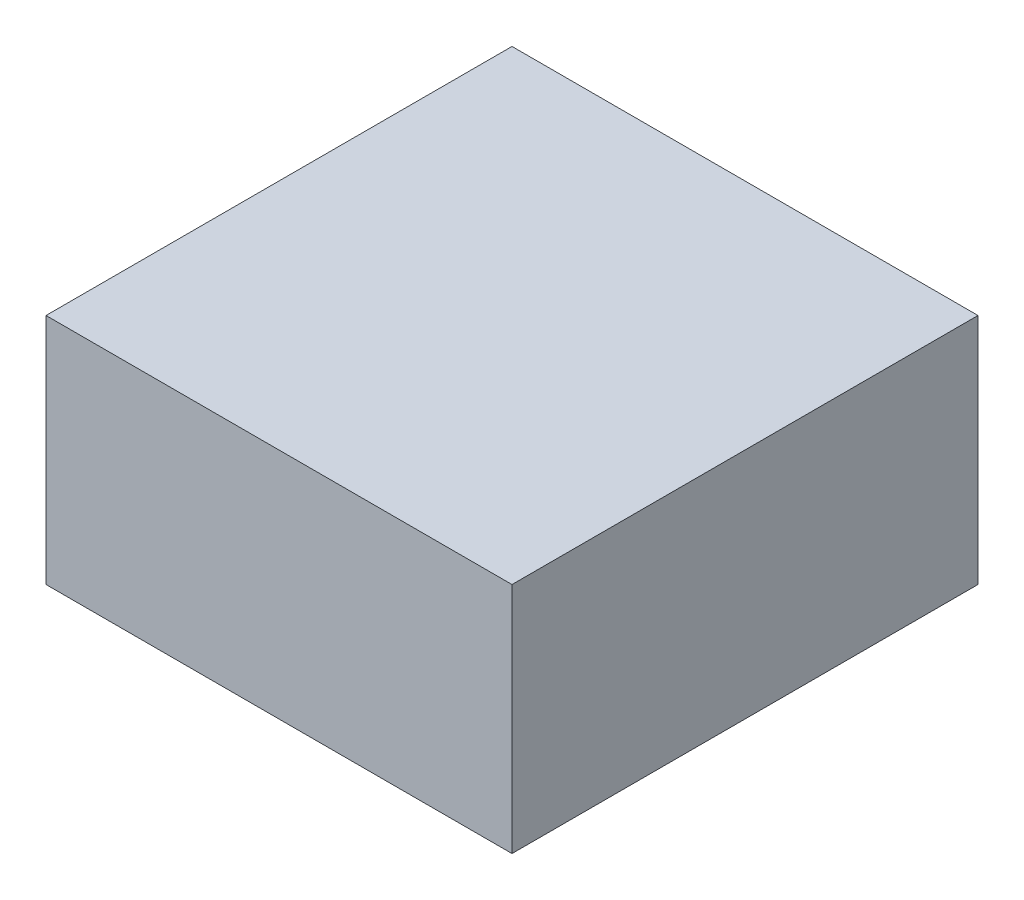
SolidWorks part; units mm, degrees
ref_plane "Front Plane" through (0, 0, 0) normal (0, 0, 1) x (1, 0, 0)
ref_plane "Top Plane" through (0, 0, 0) normal (0, 1, 0) x (1, 0, 0)
ref_plane "Right Plane" through (0, 0, 0) normal (1, 0, 0) x (0, 0, -1)
sketch "Sketch1" plane through (0, 0, 0) normal (0, 1, 0) x (1, 0, 0)
  line L1 (-43.18, 43.18) -> (43.18, 43.18)
  line L2 (-43.18, 43.18) -> (-43.18, -43.18)
  line L3 (-43.18, -43.18) -> (43.18, -43.18)
  line L4 (43.18, 43.18) -> (43.18, -43.18)
  point P4 (-43.18, 0)
  point P5 (43.18, 0)
  point P7 (0, -43.18)
  dimension "D1" = 86.36
  dimension "D2" = 86.36
extrude "Boss-Extrude1" add sketch "Sketch1" against normal blind 43.18
sketch "Sketch2" plane through (0, -43.18, 0) normal (0, -1, 0) x (-1, 0, 0)
  line L0 (43.18, 43.18) -> (43.18, -43.18) construction
  line L1 (-40.64, 40.64) -> (40.64, 40.64)
  line L2 (-40.64, 40.64) -> (-40.64, -40.64)
  line L3 (-40.64, -40.64) -> (40.64, -40.64)
  line L4 (40.64, 40.64) -> (40.64, -40.64)
  line L5 (-43.18, 43.18) -> (43.18, 43.18) construction
  point P8 (40.64, 0)
  point P9 (43.18, 0)
  point P10 (0, 40.64)
  point P11 (0, 43.18)
  dimension "D1" = 2.54
  dimension "D2" = 2.54
extrude "Cut-Extrude2" cut sketch "Sketch2" against normal offset from surface (35.56 mm away) 7.62 up to face at (0, 0, 0)
sketch "Sketch6" plane through (0, -7.62, 0) normal (0, -1, 0) x (-1, 0, 0)
  line L0 (-27.94, 38.1) -> (27.94, 38.1)
  line L1 (38.1, 27.94) -> (38.1, -27.94)
  line L2 (27.94, -38.1) -> (-27.94, -38.1)
  line L3 (-38.1, -27.94) -> (-38.1, 27.94)
  line L4 (40.64, 40.64) -> (-40.64, 40.64) construction
  line L5 (40.64, -40.64) -> (40.64, 40.64) construction
  line L6 (-40.64, 40.64) -> (-40.64, -40.64) construction
  line L7 (-40.64, -40.64) -> (40.64, -40.64) construction
  line L9 (-40.64, 40.64) -> (40.64, 40.64)
  line L10 (-40.64, 40.64) -> (-40.64, -40.64)
  line L11 (-40.64, -40.64) -> (40.64, -40.64)
  line L12 (40.64, 40.64) -> (40.64, -40.64)
  arc A0 (-30.48, 35.56) -> (-35.56, 30.48) centre (-35.56, 35.56) cw
  arc A1 (30.48, 35.56) -> (35.56, 30.48) centre (35.56, 35.56) ccw
  arc A2 (35.56, -30.48) -> (30.48, -35.56) centre (35.56, -35.56) ccw
  arc A3 (-30.48, -35.56) -> (-35.56, -30.48) centre (-35.56, -35.56) ccw
  arc A4 (-35.56, 30.48) -> (-38.1, 27.94) centre (-35.56, 27.94) ccw
  arc A5 (-35.56, -30.48) -> (-38.1, -27.94) centre (-35.56, -27.94) cw
  arc A6 (-30.48, -35.56) -> (-27.94, -38.1) centre (-27.94, -35.56) ccw
  arc A7 (30.48, -35.56) -> (27.94, -38.1) centre (27.94, -35.56) cw
  arc A8 (35.56, -30.48) -> (38.1, -27.94) centre (35.56, -27.94) ccw
  arc A9 (35.56, 30.48) -> (38.1, 27.94) centre (35.56, 27.94) cw
  arc A10 (30.48, 35.56) -> (27.94, 38.1) centre (27.94, 35.56) ccw
  arc A11 (-30.48, 35.56) -> (-27.94, 38.1) centre (-27.94, 35.56) cw
  circle A12 centre (-35.56, 35.56) radius 1.016
  circle A13 centre (35.56, 35.56) radius 1.016
  circle A14 centre (35.56, -35.56) radius 1.016
  circle A15 centre (-35.56, -35.56) radius 1.016
  point P45 (0, 0)
  point P46 (0, 0)
  point P47 (15.24, 27.94)
  point P48 (15.24, 27.94)
  point P49 (12.8505, 44.1061)
  point P50 (40.64, 27.94)
  dimension "D1" = 5.08
  dimension "D6" = 2.54
  dimension "D7" = 2.032
  dimension "D2" = 2.54
  dimension "D3" = 2.54
  dimension "D4" = 2.54
  dimension "D5" = 2.54
extrude "Boss-Extrude2" add sketch "Sketch6" along normal offset from surface (30.48 mm away) 5.08 up to face at (0, -43.18, 0)
sketch "Sketch9" plane through (-43.18, 0, 0) normal (-1, 0, 0) x (0, 0, 1)
  line L0 (17.78, -18.1026) -> (0, -27.94) construction
  line L1 (0, -27.94) -> (-17.78, -18.1026) construction
  line L2 (-43.18, 0) -> (43.18, 0) construction
  circle A0 centre (0, -27.94) radius 6.35
  circle A1 centre (-17.78, -18.1026) radius 6.35
  circle A2 centre (17.78, -18.1026) radius 6.35
  point P7 (0, 0)
  point P9 (0, 0)
  point P10 (0, -20.32)
  point P11 (16.4139, -12.3297)
  point P12 (-17.6021, -13.4373)
  point P13 (-2.1918, -25.4)
  point P14 (0, 0)
  point P15 (0, 0)
  dimension "D1" = 12.7
  dimension "D2" = 20.32
  dimension "D3" = 27.94
  dimension "D4" = 35.56
extrude "Cut-Extrude3" cut sketch "Sketch9" against normal up to surface (5.08 mm away) up to face at (-38.1, -22.86, 0)
sketch "Sketch10" plane through (-43.18, 0, 0) normal (-1, 0, 0) x (0, 0, 1)
  circle A0 centre (0, -10.16) radius 1.905
  circle A1 centre (0, -27.94) radius 6.35 construction
  dimension "D1" = 3.81
  dimension "D2" = 17.78
extrude "Cut-Extrude4" cut sketch "Sketch10" against normal up to next
